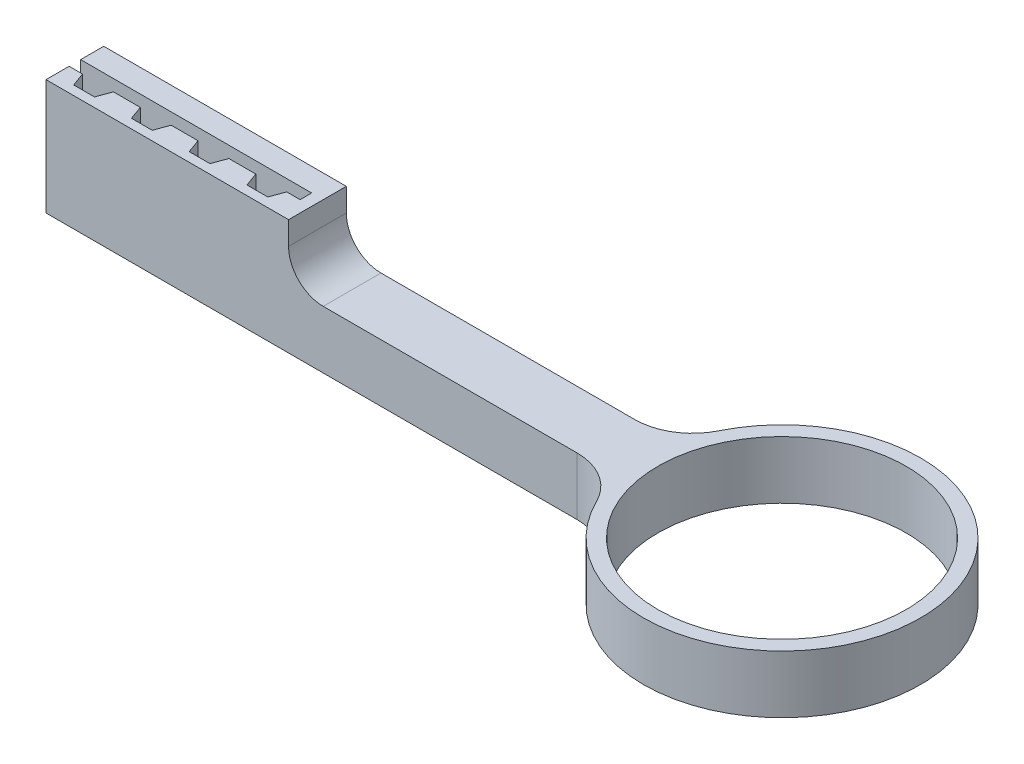
SolidWorks part; units mm, degrees
ref_plane "Спереди" through (0, 0, 0) normal (0, 0, 1) x (1, 0, 0)
ref_plane "Сверху" through (0, 0, 0) normal (0, 1, 0) x (1, 0, 0)
ref_plane "Справа" through (0, 0, 0) normal (1, 0, 0) x (0, 0, -1)
sketch "Эскиз1" plane through (0, 0, 0) normal (0, 1, 0) x (1, 0, 0)
  circle A0 centre (0, 0) radius 10.75
  circle A1 centre (0, 0) radius 12
  dimension "D1" = 21.5
  dimension "D2" = 24
extrude "ring" add sketch "Эскиз1" along normal blind 5
sketch "Эскиз2" plane through (0, 0, 0) normal (0, 1, 0) x (1, 0, 0)
  line L0 (34.0214, 0) -> (-42.1067, 0) construction
  line L2 (-11.225, 2.5) -> (-61.225, 2.5)
  line L3 (-11.225, 2.5) -> (-11.225, -2.5)
  line L4 (-11.225, -2.5) -> (-61.225, -2.5)
  line L5 (-61.225, 2.5) -> (-61.225, -2.5)
  circle A0 centre (0, 0) radius 11.5 construction
  dimension "D3" = 23
  dimension "D1" = 2.5
  dimension "D2" = 5
  dimension "D4" = 50
extrude "stick" add sketch "Эскиз2" along normal blind 5
sketch "Эскиз3" plane through (0, 0, 0) normal (0, 1, 0) x (1, 0, 0)
  line L0 (-61.225, -2.5) -> (-11.7367, -2.5) construction
  line L1 (-61.225, 2.5) -> (-40.225, 2.5)
  line L2 (-61.225, 2.5) -> (-61.225, -2.5)
  line L3 (-61.225, -2.5) -> (-40.225, -2.5)
  line L4 (-40.225, 2.5) -> (-40.225, -2.5)
  dimension "D1" = 21
extrude "key" add sketch "Эскиз3" along normal blind 10
fillet "Скругление1" radius 5 2 edges at (-11.7367, 2.5, 2.5) (-11.7367, 2.5, -2.5)
ref_plane "Плоскость1" through (0, 2.5, 0) normal (0, 1, 0) x (-1, 0, 0)
sketch "Эскиз4" plane through (0, 2.5, 0) normal (0, 1, 0) x (1, 0, 0)
  line L0 (-61.225, 0) -> (-40.225, 0) construction
  line L1 (-61.225, 2.5) -> (-61.225, -2.5) construction
  line L2 (-40.225, -2.5) -> (-40.225, 2.5) construction
  line L3 (-61.225, 0.5) -> (-41.225, 0.5)
  line L4 (-59.625, -1.7) -> (-57.825, -1.7)
  line L5 (-60.0617, -0.5) -> (-41.2194, -0.5) construction
  line L6 (-60.0617, -0.5) -> (-59.625, -1.7) construction
  line L7 (-60.0617, -0.5) -> (-59.625, -1.7)
  line L8 (-57.825, -1.7) -> (-57.3882, -0.5)
  line L9 (-58.725, 1.0157) -> (-58.725, -3.4603) construction
  line L10 (-60.0617, -0.5) -> (-61.225, -0.5)
  line L11 (-57.3882, -0.5) -> (-56.225, -0.5)
  line L12 (-61.225, 0.5) -> (-61.225, -0.5)
  line L13 (-55.0617, -0.5) -> (-56.225, -0.5)
  line L14 (-55.0617, -0.5) -> (-54.625, -1.7)
  line L15 (-54.625, -1.7) -> (-52.825, -1.7)
  line L16 (-52.825, -1.7) -> (-52.3882, -0.5)
  line L17 (-52.3882, -0.5) -> (-51.225, -0.5)
  line L18 (-50.0617, -0.5) -> (-51.225, -0.5)
  line L19 (-50.0617, -0.5) -> (-49.625, -1.7)
  line L20 (-49.625, -1.7) -> (-47.825, -1.7)
  line L21 (-47.825, -1.7) -> (-47.3882, -0.5)
  line L22 (-47.3882, -0.5) -> (-46.225, -0.5)
  line L23 (-45.0617, -0.5) -> (-46.225, -0.5)
  line L24 (-45.0617, -0.5) -> (-44.625, -1.7)
  line L25 (-44.625, -1.7) -> (-42.825, -1.7)
  line L26 (-42.825, -1.7) -> (-42.3882, -0.5)
  line L27 (-42.3882, -0.5) -> (-41.225, -0.5)
  line L28 (-41.225, 0.5) -> (-41.225, -0.5)
  point P12 (-58.725, -1.7)
  dimension "D1" = 1.8
  dimension "D2" = 0.5
  dimension "D3" = 0.5
  dimension "D4" = 1.2
  dimension "D5" = 110
  dimension "D6" = 5
  dimension "D7" = 40
fillet "Скругление5" radius 3 1 edges at (-40.225, 5, 0)
extrude "Вытянуть1" cut sketch "Эскиз4" against normal through all and the other way through all
